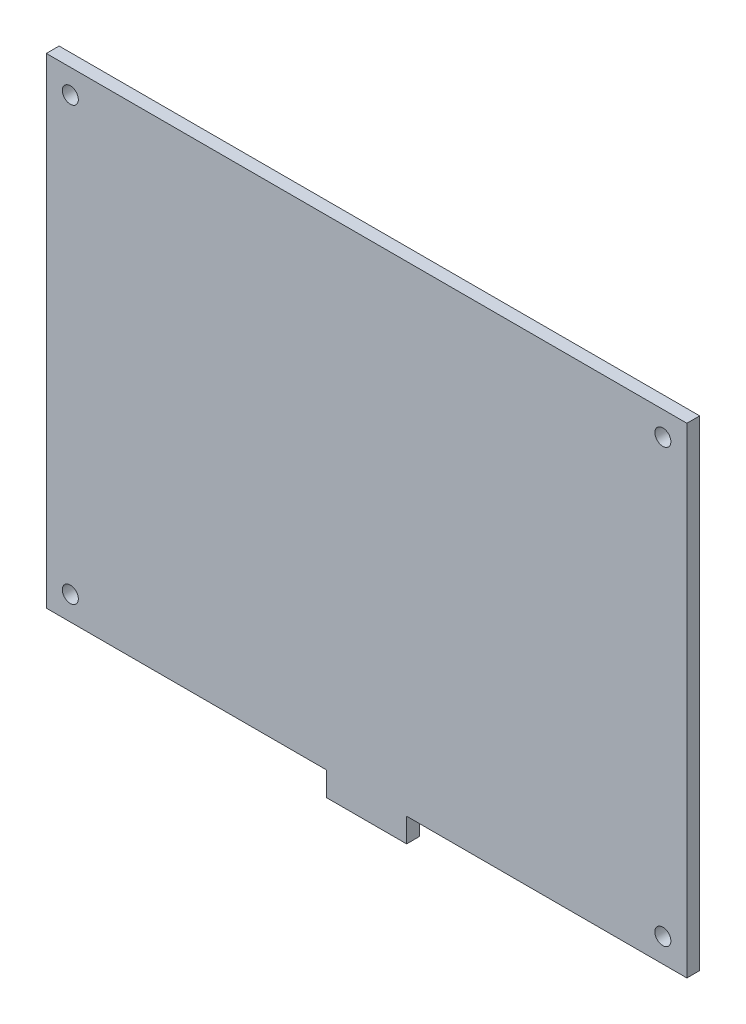
SolidWorks part; units mm, degrees
ref_plane "前视基准面" through (0, 0, 0) normal (0, 0, 1) x (1, 0, 0)
ref_plane "上视基准面" through (0, 0, 0) normal (0, 1, 0) x (1, 0, 0)
ref_plane "右视基准面" through (0, 0, 0) normal (1, 0, 0) x (0, 0, -1)
other "Configuration Table"
sketch "草图1" plane through (0, 0, 0) normal (0, 0, 1) x (1, 0, 0)
  line L61 (-40, 30) -> (40, 30)
  line L62 (-40, 30) -> (-40, -30)
  line L63 (-40, -30) -> (40, -30)
  line L64 (40, 30) -> (40, -30)
  line L65 (-5, -30) -> (5, -30)
  line L66 (-5, -30) -> (-5, -33)
  line L67 (-5, -33) -> (5, -33)
  line L68 (5, -30) -> (5, -33)
  circle A0 centre (-37, 27) radius 1
  circle A1 centre (37, 27) radius 1
  circle A2 centre (37, -27) radius 1
  circle A3 centre (-37, -27) radius 1
  point P4 (0, 30)
  point P5 (-40, 0)
  point P18 (0, -33)
  dimension "D4" = 3
  dimension "D1" = 60
  dimension "D2" = 80
  dimension "D3" = 2
  dimension "D6" = 3
  dimension "D5" = 3
  dimension "D7" = 3
  dimension "D8" = 10
  dimension "D9" = 3
extrude "凸台-拉伸1" add sketch "草图1" along normal blind 1.6 contours L63 L64 L61 L62 | A3 | A0 | A1 | A2 | L67 L68 L65 L66
